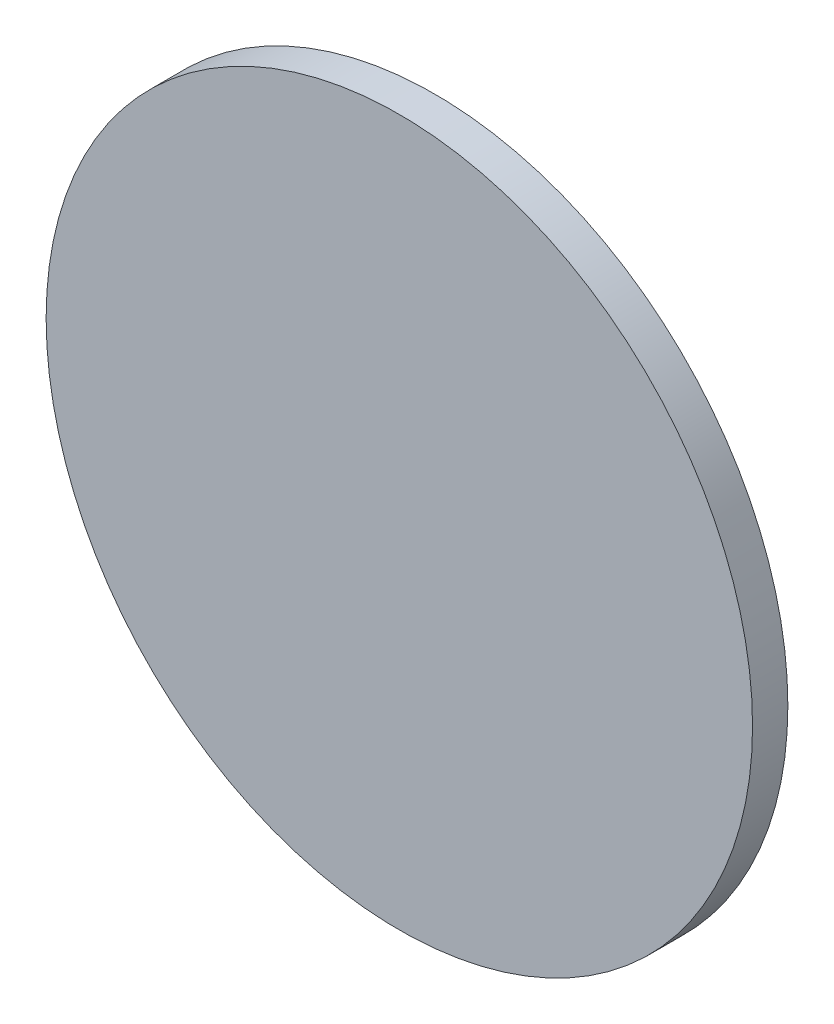
SolidWorks part; units mm, degrees
ref_plane "Front Plane" through (0, 0, 0) normal (0, 0, 1) x (1, 0, 0)
ref_plane "Top Plane" through (0, 0, 0) normal (0, 1, 0) x (1, 0, 0)
ref_plane "Right Plane" through (0, 0, 0) normal (1, 0, 0) x (0, 0, -1)
sketch "Sketch2" plane through (0, 0, 0) normal (0, 0, 1) x (1, 0, 0)
  circle A0 centre (0, 0) radius 40
  dimension "D1" = 80
extrude "Boss-Extrude1" add sketch "Sketch2" along normal blind 4
